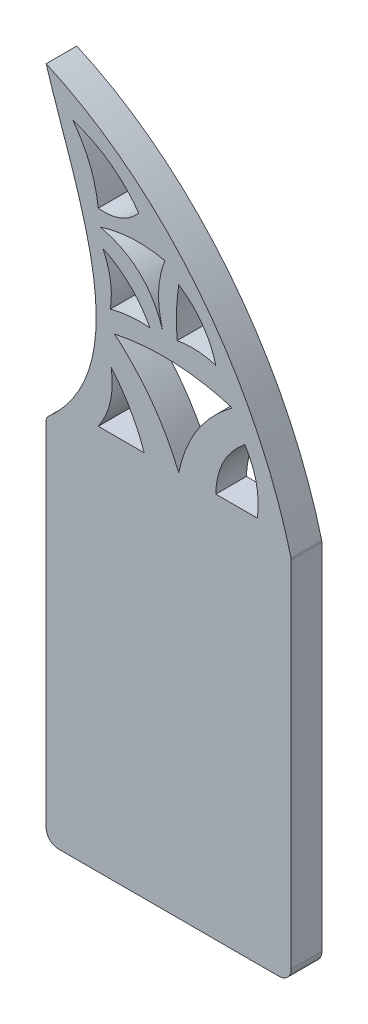
SolidWorks part; units mm, degrees
ref_plane "Front Plane" through (0, 0, 0) normal (0, 0, 1) x (1, 0, 0)
ref_plane "Top Plane" through (0, 0, 0) normal (0, 1, 0) x (1, 0, 0)
ref_plane "Right Plane" through (0, 0, 0) normal (1, 0, 0) x (0, 0, -1)
sketch "Sketch1" plane through (0, 0, 0) normal (0, 0, 1) x (1, 0, 0)
  line L1 (0, 0) -> (101.6, 0)
  line L2 (0, 0) -> (0, 152.4)
  line L3 (0, 152.4) -> (101.6, 152.4)
  line L4 (101.6, 0) -> (101.6, 152.4)
  dimension "D1" = 101.6
  dimension "D2" = 152.4
extrude "Boss-Extrude1" add sketch "Sketch1" along normal blind 12.7 contours L2 L1 L4 L3
sketch "Sketch2" plane through (0, 0, 0) normal (0, 0, 1) x (1, 0, 0)
  line L0 (0, 152.4) -> (0, 279.4) construction
  line L1 (0, 152.4) -> (101.6, 152.4)
  line L3 (40.6766, 160.02) -> (21.6029, 160.02)
  line L4 (70.3278, 160.02) -> (87.5465, 160.02)
  spline S0 degree 3 poles (0, 279.4) (51.2861, 256.55) (87.8369, 205.9579) (101.6, 152.4) knots 0 0 0 0 1 1 1 1
  spline S1 degree 3 poles (0, 152.4) (39.7901, 186.8391) (12.3098, 238.8455) (0, 279.4) knots 0 0 0 0 1 1 1 1
  spline S2 degree 2 poles (26.9805, 183.8137) (28.9588, 170.8375) (21.6029, 160.02) knots 0 0 0 1 1 1
  spline S3 degree 2 poles (82.3961, 183.8137) (89.3396, 172.7738) (87.5465, 160.02) knots 0 0 0 1 1 1
  spline S4 degree 2 poles (23.5161, 224.8619) (28.2353, 215.2193) (26.6057, 204.5822) knots 0 0 0 1 1 1
  spline S5 degree 2 poles (54.9771, 227.5573) (66.6459, 219.8522) (70.3283, 206.2775) knots 0 0 0 1 1 1
  spline S6 degree 2 poles (21.6029, 238.3231) (31.8648, 237.2845) (38.4123, 244.9499) knots 0 0 0 1 1 1
  spline S7 degree 2 poles (26.9805, 183.8137) (36.1385, 173.1751) (40.6766, 160.02) knots 0 0 0 1 1 1
  spline S8 degree 2 poles (82.3961, 183.8137) (70.6714, 174.6636) (70.3278, 160.02) knots 0 0 0 1 1 1
  spline S9 degree 2 poles (54.9771, 160.02) (46.0835, 181.5476) (28.3421, 196.5298) knots 0 0 0 1 1 1
  spline S10 degree 2 poles (54.9771, 160.02) (59.3747, 181.4006) (77.1872, 194.3635) knots 0 0 0 1 1 1
  spline S11 degree 2 poles (28.3421, 196.5298) (53.0178, 201.7323) (77.1872, 194.3635) knots 0 0 0 1 1 1
  spline S12 degree 2 poles (26.6057, 204.5822) (34.7004, 206.7929) (43.0535, 206.088) knots 0 0 0 1 1 1
  spline S13 degree 2 poles (43.0535, 206.088) (36.2398, 218.9127) (23.5161, 224.8619) knots 0 0 0 1 1 1
  spline S14 degree 2 poles (70.3283, 206.2775) (62.3616, 208.669) (54.2871, 207.1099) knots 0 0 0 1 1 1
  spline S15 degree 2 poles (54.2871, 207.1099) (53.4821, 217.3917) (54.9771, 227.5573) knots 0 0 0 1 1 1
  spline S16 degree 2 poles (48.4004, 207.5354) (42.0542, 227.5662) (22.3756, 231.9373) knots 0 0 0 1 1 1
  spline S17 degree 2 poles (48.4004, 207.5354) (44.3936, 220.7345) (49.2258, 233.3158) knots 0 0 0 1 1 1
  spline S18 degree 2 poles (49.2258, 233.3158) (35.6412, 236.2679) (22.3756, 231.9373) knots 0 0 0 1 1 1
  spline S19 degree 2 poles (21.6029, 238.3231) (19.952, 252.9745) (11.0947, 264.6015) knots 0 0 0 1 1 1
  spline S20 degree 2 poles (11.0947, 264.6015) (28.0538, 259.2958) (38.4123, 244.9499) knots 0 0 0 1 1 1
  dimension "D1" = 127
extrude "Boss-Extrude3" add sketch "Sketch2" along normal blind 12.7 contours S1 L1 S0 S18 S17 S16 S13 S12 S4 S8 S3 L4 S2 S7 L3 S9 S11 S10 S14 S15 S5 S19 S20 S6
fillet "Fillet1" radius 2.54 2 edges at (101.6, 152.4, 6.35) (0, 152.4, 6.35)
fillet "Fillet2" radius 5.08 2 edges at (101.6, 0, 6.35) (0, 0, 6.35)
